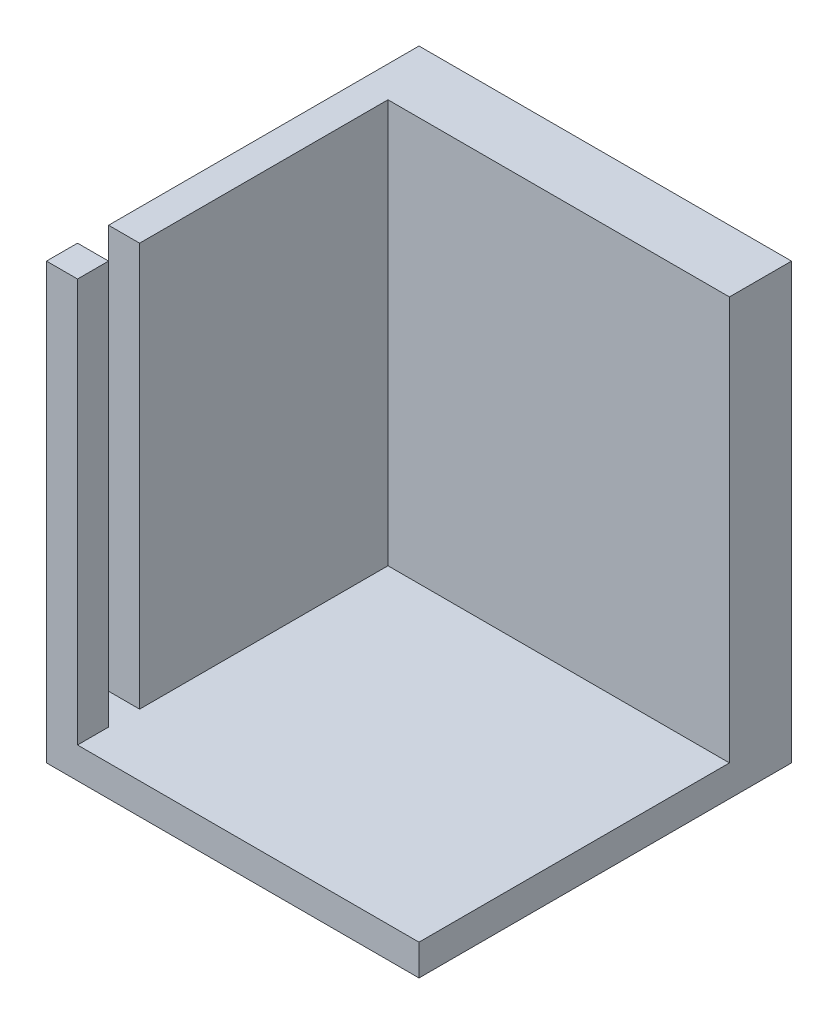
SolidWorks part; units mm, degrees
ref_plane "정면" through (0, 0, 0) normal (0, 0, 1) x (1, 0, 0)
ref_plane "윗면" through (0, 0, 0) normal (0, 1, 0) x (1, 0, 0)
ref_plane "우측면" through (0, 0, 0) normal (1, 0, 0) x (0, 0, -1)
sketch "Sketch1" plane through (0, 0, 0) normal (0, 1, 0) x (1, 0, 0)
  line L1 (0, 0) -> (670, 0)
  line L2 (0, 0) -> (0, 120)
  line L3 (0, 120) -> (670, 120)
  line L4 (670, 0) -> (670, 120)
  dimension "700" = 670
  dimension "D2" = 120
extrude "Boss-Extrude1" add sketch "Sketch1" along normal blind 530
sketch "Sketch2" plane through (0, 0, 0) normal (0, 0, 1) x (1, 0, 0)
  line L0 (0, 530) -> (0, 0) construction
  line L1 (10, 280) -> (110, 280)
  line L2 (10, 280) -> (10, 480)
  line L3 (10, 480) -> (110, 480)
  line L4 (110, 280) -> (110, 480)
  line L5 (0, 0) -> (670, 0) construction
  line L6 (120, 280) -> (120, 480)
  line L7 (120, 280) -> (220, 280)
  line L8 (220, 280) -> (220, 480)
  line L9 (120, 480) -> (220, 480)
  line L10 (230, 280) -> (230, 480)
  line L11 (230, 280) -> (330, 280)
  line L12 (330, 280) -> (330, 480)
  line L13 (230, 480) -> (330, 480)
  line L14 (340, 280) -> (340, 480)
  line L15 (340, 280) -> (440, 280)
  line L16 (440, 280) -> (440, 480)
  line L17 (340, 480) -> (440, 480)
  line L18 (450, 280) -> (450, 480)
  line L19 (450, 280) -> (550, 280)
  line L20 (550, 280) -> (550, 480)
  line L21 (450, 480) -> (550, 480)
  line L22 (560, 280) -> (560, 480)
  line L23 (560, 280) -> (660, 280)
  line L24 (660, 280) -> (660, 480)
  line L25 (560, 480) -> (660, 480)
  line L27 (10, 10) -> (660, 10)
  line L28 (10, 10) -> (10, 260)
  line L29 (10, 260) -> (660, 260)
  line L30 (660, 10) -> (660, 260)
  line L31 (0, 530) -> (670, 530) construction
  point P6 (10, 380)
  dimension "D1" = 100
  dimension "D2" = 200
  dimension "D3" = 10
  dimension "D4" = 50
  dimension "D6" = 10
  dimension "D7" = 20
  dimension "D5" = 6
extrude "Cut-Extrude1" cut sketch "Sketch2" against normal blind 100
sketch "Sketch3" plane through (0, 530, 0) normal (0, 1, 0) x (1, 0, 0)
  line L1 (670, 120) -> (0, 120) construction
  line L2 (0, 120) -> (0, 0) construction
  circle A0 centre (60, 60) radius 50
  circle A1 centre (170, 60) radius 50
  circle A2 centre (280, 60) radius 50
  circle A3 centre (390, 60) radius 50
  circle A4 centre (500, 60) radius 50
  circle A5 centre (610, 60) radius 50
  dimension "D1" = 100
  dimension "D2" = 10
  dimension "D3" = 10
  dimension "D4" = 6
extrude "Cut-Extrude2" cut sketch "Sketch3" against normal blind 260
hole_wizard "Ø12.0 (12) Diameter Hole2" positions "3DSketch1" profile "Sketch7" hole size "Ø12.0" standard "Ansi Metric"
sketch3d "3DSketch1"
  point P0 (59.7046, 270, -102.4117)
  point P2 (171.5567, 270, -102.6076)
  point P4 (280.8723, 270, -102.3969)
  point P6 (391.0687, 270, -102.7535)
  point P8 (500.7133, 270, -101.754)
  point P10 (609.5165, 270, -101.1227)
sketch "Sketch7" plane through (59.7046, 270, -102.4117) normal (1, 0, 0) x (0, 0, 1)
  line L0 (0, 0) -> (0, 33.6052)
  line L1 (0, 33.6052) -> (6, 30)
  line L2 (6, 30) -> (6, 0)
  line L5 (6, 0) -> (0, 0)
  line L10 (0, 33.6052) -> (-6, 30) construction
  line L11 (0, -6.35) -> (0, 107.95) construction
  dimension "구멍 지름" = 12
  dimension "구멍 깊이" = 30
  dimension "드릴 각도" = 118
sketch "Sketch8" plane through (0, 0, 0) normal (0, 0, 1) x (1, 0, 0)
  line L0 (660, 280) -> (660, 480) construction
  line L1 (10, 280) -> (660, 280)
  line L2 (10, 280) -> (10, 330)
  line L3 (10, 330) -> (660, 330)
  line L4 (660, 280) -> (660, 330)
  dimension "D1" = 50
extrude "Boss-Extrude2" add sketch "Sketch8" against normal blind 5
sketch "Sketch9" plane through (670, 0, 0) normal (1, 0, 0) x (0, 0, -1)
  line L0 (0, 530) -> (0, 0) construction
  line L1 (10, 10) -> (20, 10)
  line L2 (10, 10) -> (10, 260)
  line L3 (10, 260) -> (20, 260)
  line L4 (20, 10) -> (20, 260)
  line L5 (0, 0) -> (120, 0) construction
  dimension "D1" = 10
  dimension "D2" = 10
  dimension "D3" = 10
  dimension "D4" = 250
extrude "Cut-Extrude3" cut sketch "Sketch9" against normal blind 717
sketch "Sketch10" plane through (0, 10, 0) normal (0, 1, 0) x (1, 0, 0)
  line L0 (670, 120) -> (0, 120) construction
  line L1 (365, 61.9436) -> (350, 87.9243)
  line L2 (350, 87.9243) -> (320, 87.9243)
  line L3 (320, 87.9243) -> (305, 61.9436)
  line L4 (305, 61.9436) -> (320, 35.9628)
  line L5 (320, 35.9628) -> (350, 35.9628)
  line L6 (350, 35.9628) -> (365, 61.9436)
  line L7 (0, 120) -> (0, 0) construction
  circle A0 centre (335, 61.9436) radius 25.9808 construction
  dimension "D1" = 60
  dimension "D2" = 305
extrude "Cut-Extrude4" cut sketch "Sketch10" against normal blind 5
sketch "Sketch11" plane through (0, 0, -100) normal (0, 0, 1) x (1, 0, 0)
  line L0 (10, 10) -> (660, 10) construction
  line L1 (250, 10) -> (260, 10)
  line L2 (250, 10) -> (250, 110)
  line L3 (250, 110) -> (260, 110)
  line L4 (260, 10) -> (260, 110)
  line L5 (660, 10) -> (660, 260) construction
  line L6 (410, 10) -> (420, 10)
  line L7 (410, 10) -> (410, 110)
  line L8 (410, 110) -> (420, 110)
  line L9 (420, 10) -> (420, 110)
  line L10 (25, 198.4569) -> (325, 145.5588)
  line L11 (325, 145.5588) -> (325, 122.0178)
  line L12 (325, 122.0178) -> (345, 122.0178)
  line L13 (345, 122.0178) -> (345, 145.5588)
  line L14 (345, 145.5588) -> (645, 198.4569)
  line L15 (645, 198.4569) -> (25, 198.4569)
  point P18 (345, 133.7883)
  dimension "D1" = 10
  dimension "D2" = 10
  dimension "D3" = 100
  dimension "D4" = 100
  dimension "D5" = 150
  dimension "D6" = 240
  dimension "D7" = 20
  dimension "D8" = 65
  dimension "D9" = 100
  dimension "D10" = 620
  dimension "D11" = 100
extrude "Boss-Extrude3" add sketch "Sketch11" along normal blind 78 separate body
sketch "Sketch12" plane through (0, 0, -100) normal (0, 0, 1) x (1, 0, 0)
  line L0 (660, 260) -> (10, 260) construction
  line L1 (75.1986, 260) -> (95.1986, 260)
  line L2 (75.1986, 260) -> (75.1986, 230)
  line L3 (75.1986, 230) -> (95.1986, 230)
  line L4 (95.1986, 260) -> (95.1986, 230)
  line L5 (65.1986, 260) -> (65.1986, 240) construction
  line L6 (185.1986, 260) -> (185.1986, 230)
  line L7 (185.1986, 260) -> (205.1986, 260)
  line L8 (205.1986, 260) -> (205.1986, 230)
  line L9 (185.1986, 230) -> (205.1986, 230)
  line L10 (295.1986, 260) -> (295.1986, 230)
  line L11 (295.1986, 260) -> (315.1986, 260)
  line L12 (315.1986, 260) -> (315.1986, 230)
  line L13 (295.1986, 230) -> (315.1986, 230)
  line L14 (405.1986, 260) -> (405.1986, 230)
  line L15 (405.1986, 260) -> (425.1986, 260)
  line L16 (425.1986, 260) -> (425.1986, 230)
  line L17 (405.1986, 230) -> (425.1986, 230)
  line L18 (515.1986, 260) -> (515.1986, 230)
  line L19 (515.1986, 260) -> (535.1986, 260)
  line L20 (535.1986, 260) -> (535.1986, 230)
  line L21 (515.1986, 230) -> (535.1986, 230)
  line L22 (625.1986, 260) -> (625.1986, 230)
  line L23 (625.1986, 260) -> (645.1986, 260)
  line L24 (645.1986, 260) -> (645.1986, 230)
  line L25 (625.1986, 230) -> (645.1986, 230)
  dimension "D1" = 20
  dimension "D2" = 30
  dimension "D3" = 10
  dimension "D4" = 6
extrude "Cut-Extrude5" cut sketch "Sketch12" against normal blind 80
sketch "Sketch15" plane through (345, 0, 0) normal (1, 0, 0) x (0, 0, -1)
  line L0 (20, 10) -> (20, 260) construction
  line L1 (20, 121.4638) -> (50, 121.4638)
  line L2 (20, 121.4638) -> (20, 145)
  line L3 (20, 145) -> (50, 145)
  line L4 (50, 121.4638) -> (50, 145)
  line L5 (120, 530) -> (120, 0) construction
  line L6 (100, 116.0134) -> (70, 116.0134)
  line L7 (100, 116.0134) -> (100, 145)
  line L8 (100, 145) -> (70, 145)
  line L9 (70, 116.0134) -> (70, 145)
  line L10 (20, 260) -> (10, 260) construction
  dimension "D1" = 20
  dimension "D2" = 20
  dimension "D3" = 115
  dimension "D4" = 30
extrude "Cut-Extrude7" cut sketch "Sketch15" against normal blind 35
shell "Shell1" thickness 3
sketch "Sketch16" plane through (0, 122.0178, 0) normal (0, -1, 0) x (1, 0, 0)
  line L0 (345, -50) -> (325, -50) construction
  line L1 (328, -53) -> (342, -53)
  line L2 (328, -53) -> (328, -67)
  line L3 (328, -67) -> (342, -67)
  line L4 (342, -53) -> (342, -67)
  line L5 (325, -50) -> (325, -70) construction
  line L6 (345, -50) -> (345, -70) construction
  line L7 (325, -70) -> (345, -70) construction
  dimension "D1" = 3
  dimension "D2" = 3
  dimension "D3" = 3
  dimension "D4" = 3
extrude "Cut-Extrude8" cut sketch "Sketch16" against normal blind 35
sketch "Sketch17" plane through (0, 0, 0) normal (0, 0, 1) x (1, 0, 0)
  text T0 "<b>DIFF_USER</b>" font "Britannic Bold" height in points 72
extrude "Boss-Extrude4" add sketch "Sketch17" along normal blind 5
sketch "Sketch18" plane through (0, 0, 0) normal (0, 0, 1) x (1, 0, 0)
  line L0 (0, 530) -> (670, 530) construction
  line L1 (0, 530) -> (670, 530)
  line L2 (0, 530) -> (0, 280)
  line L3 (0, 280) -> (670, 280)
  line L4 (670, 530) -> (670, 280)
  line L5 (670, 530) -> (670, 0) construction
  line L6 (0, 0) -> (670, 0) construction
  dimension "D1" = 280
extrude "Cut-Extrude10" cut sketch "Sketch18" against normal through all both and the other way through all
delete or keep bodies "Body-Delete/Keep 1" type delete bodies bodies 112
delete or keep bodies "Body-Delete/Keep 2" type delete bodies bodies 109
delete or keep bodies "Body-Delete/Keep 3" type delete bodies bodies 115
sketch "Sketch19" plane through (0, 0, -100) normal (0, 0, 1) x (1, 0, 0)
  line L0 (670, 280) -> (0, 280) construction
  line L1 (0, 0) -> (120, 0)
  line L2 (0, 0) -> (0, 280)
  line L3 (0, 280) -> (120, 280)
  line L4 (120, 0) -> (120, 280)
  line L5 (670, 280) -> (670, 0) construction
  line L6 (120, 280) -> (670, 280)
  line L7 (120, 280) -> (120, 0)
  line L8 (120, 0) -> (670, 0)
  line L9 (670, 280) -> (670, 0)
  line L10 (670, 0) -> (0, 0) construction
  dimension "D1" = 120
extrude "Cut-Extrude11" cut sketch "Sketch19" against normal through all both and the other way through all contours L9 L6 L4 L8
sketch "Sketch20" plane through (0, 0, -100) normal (0, 0, 1) x (1, 0, 0)
  line L0 (120, 260) -> (120, 10) construction
  line L1 (0, 280) -> (120, 280)
  line L2 (0, 280) -> (0, 140)
  line L3 (0, 140) -> (120, 140)
  line L4 (120, 280) -> (120, 140)
  dimension "D1" = 140
extrude "Cut-Extrude12" cut sketch "Sketch20" against normal through all both and the other way through all
